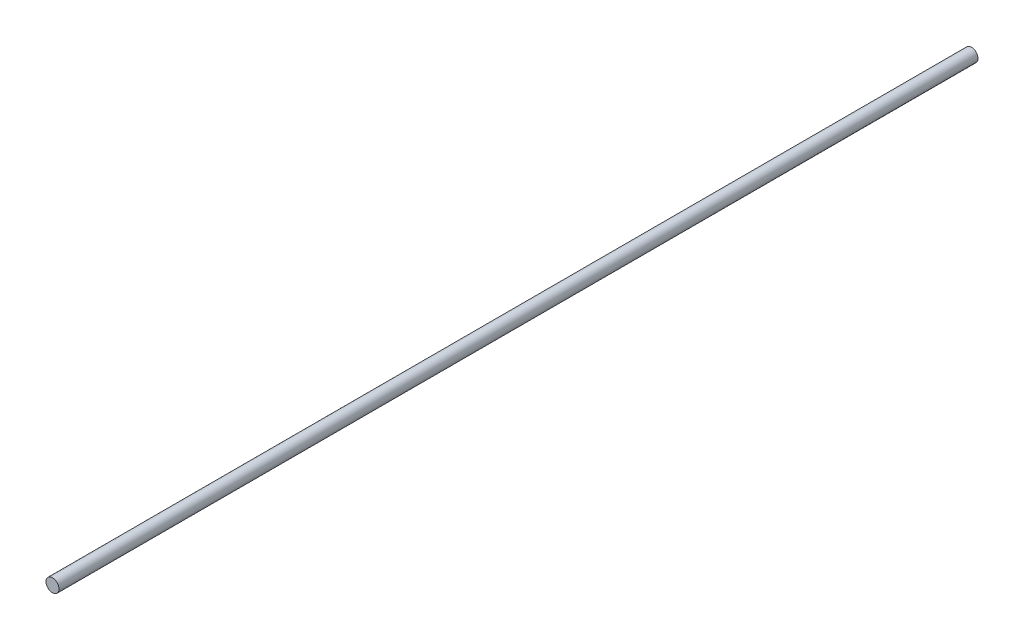
SolidWorks part; units mm, degrees
material "6063-T1"
ref_plane "Front Plane" through (0, 0, 0) normal (0, 0, 1) x (1, 0, 0)
ref_plane "Top Plane" through (0, 0, 0) normal (0, 1, 0) x (1, 0, 0)
ref_plane "Right Plane" through (0, 0, 0) normal (1, 0, 0) x (0, 0, -1)
sketch "Sketch1" plane through (0, 0, 0) normal (0, 0, 1) x (1, 0, 0)
  circle A0 centre (0, 0) radius 6.35
  dimension "D1" = 12.7
extrude "Boss-Extrude1" add sketch "Sketch1" along normal blind 897.1354 contours A0
equation "\"d\" = 0.5in"
equation "\"deflection\" = 0.009in"
equation "\"a\" = \"d\" * \"d\" * pi * 0.25"
equation "\"E\" = 68900"
equation "\"L\"= \"deflection\" * \"E\" * \"a\" / \"F\""
equation "\"F\"= 2224"
equation "\"D1@Boss-Extrude1\"=\"L\""
equation "\"D1@Sketch1\"=\"d\""
